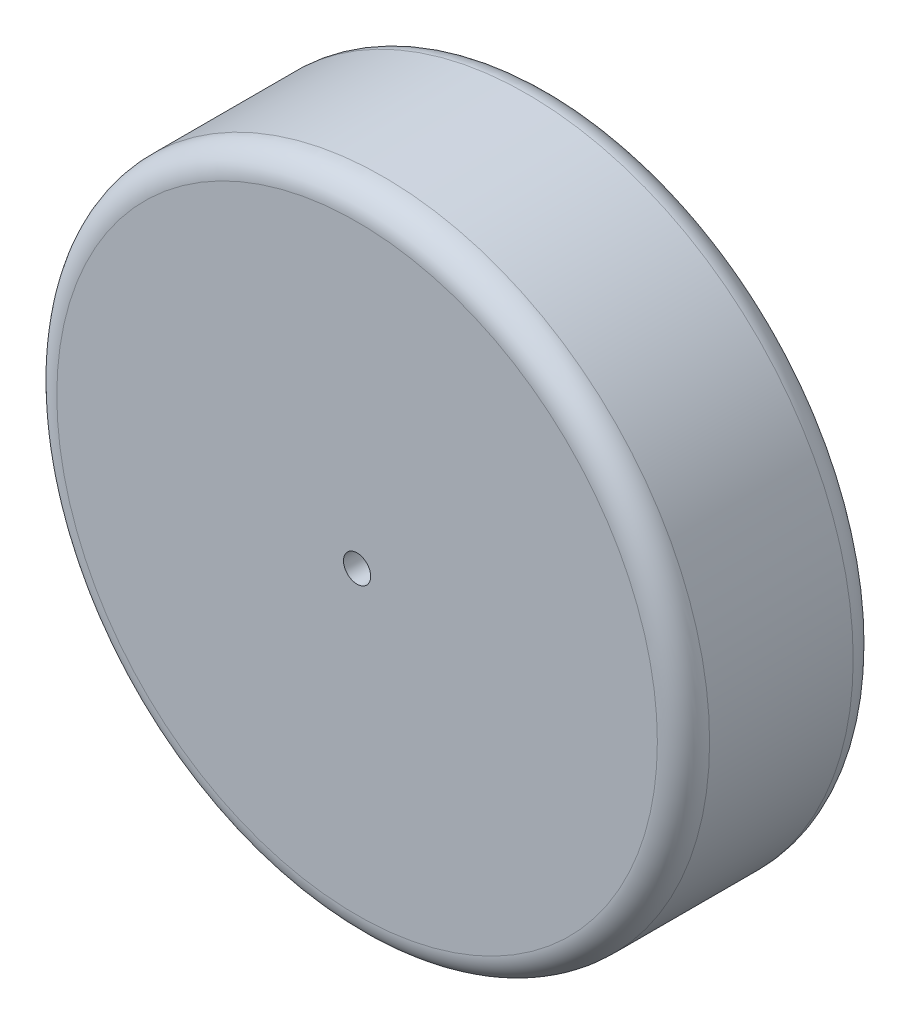
SolidWorks part; units mm, degrees
ref_plane "Front Plane" through (0, 0, 0) normal (0, 0, 1) x (1, 0, 0)
ref_plane "Top Plane" through (0, 0, 0) normal (0, 1, 0) x (1, 0, 0)
ref_plane "Right Plane" through (0, 0, 0) normal (1, 0, 0) x (0, 0, -1)
sketch "Sketch1" plane through (0, 0, 0) normal (0, 0, 1) x (1, 0, 0)
  line L0 (0, 0) -> (0, 25)
  circle A0 centre (0, 0) radius 25
  dimension "D1" = 50
extrude "Boss-Extrude1" add sketch "Sketch1" along normal blind 15 contours A0
fillet "Fillet1" radius 2 2 edges at (25, 0, 15) (25, 0, 0)
sketch "Sketch7" plane through (0, 0, 15) normal (0, 0, 1) x (1, 0, 0)
  circle A0 centre (0, 0) radius 1.04
extrude "Cut-Extrude2" cut sketch "Sketch7" against normal through all
ref_plane "Plane1" through (0, 0, 7.5) normal (0, 0, -1) x (-1, 0, 0)
